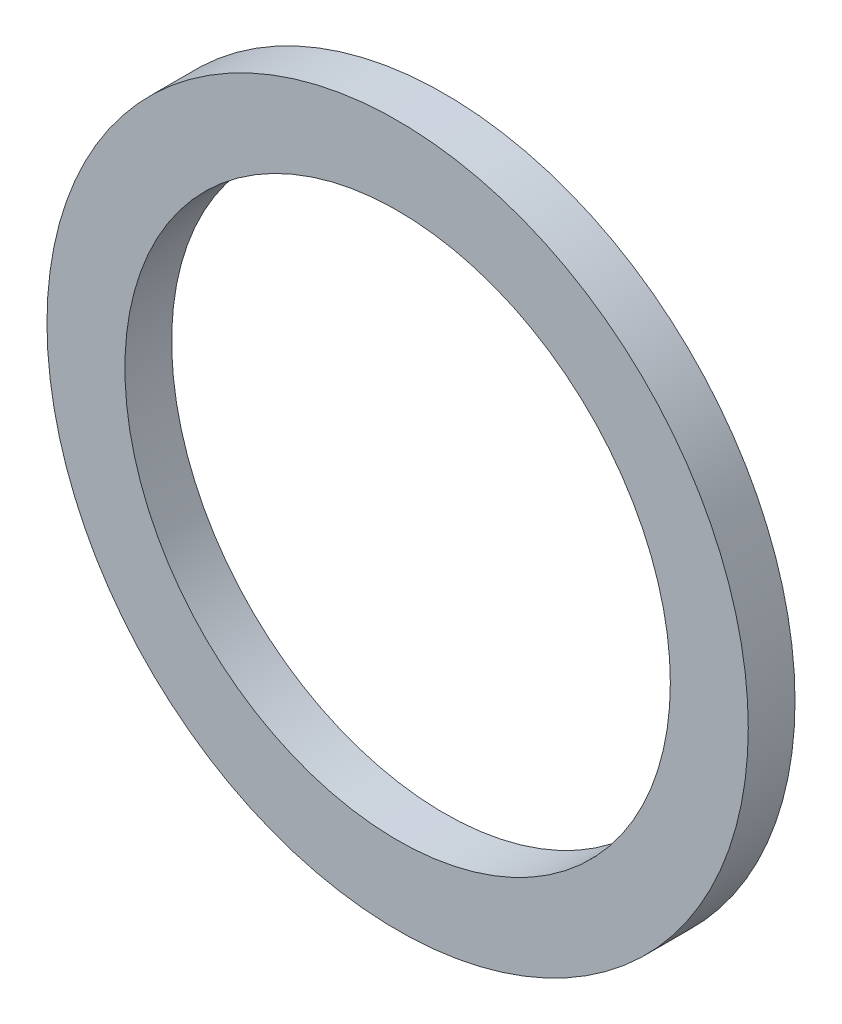
SolidWorks part; units mm, degrees
material "AISI 4130 Steel, normalized at 870C"
ref_plane "Front Plane" through (0, 0, 0) normal (0, 0, 1) x (1, 0, 0)
ref_plane "Top Plane" through (0, 0, 0) normal (0, 1, 0) x (1, 0, 0)
ref_plane "Right Plane" through (0, 0, 0) normal (1, 0, 0) x (0, 0, -1)
sketch "Sketch1" plane through (0, 0, 0) normal (0, 0, 1) x (1, 0, 0)
  circle A0 centre (0, 0) radius 22.5
  circle A1 centre (0, 0) radius 17.5
  dimension "D1" = 45
  dimension "D2" = 35
extrude "Boss-Extrude1" add sketch "Sketch1" along normal blind 2
sketch "Sketch2" plane through (0, 0, 0) normal (0, 0, -1) x (-1, 0, 0)
  circle A1 centre (0, 0) radius 22.5
  circle A2 centre (0, 0) radius 22.5
  dimension "D1" = 0
extrude "Boss-Extrude2" add sketch "Sketch2" along normal blind 1
sketch "Sketch3" plane through (0, 0, 0) normal (0, 0, 1) x (1, 0, 0)
  circle A1 centre (0, 0) radius 17.5
  circle A2 centre (0, 0) radius 17.5
  dimension "D1" = 0
extrude "Cut-Extrude1" cut sketch "Sketch3" against normal blind 1
